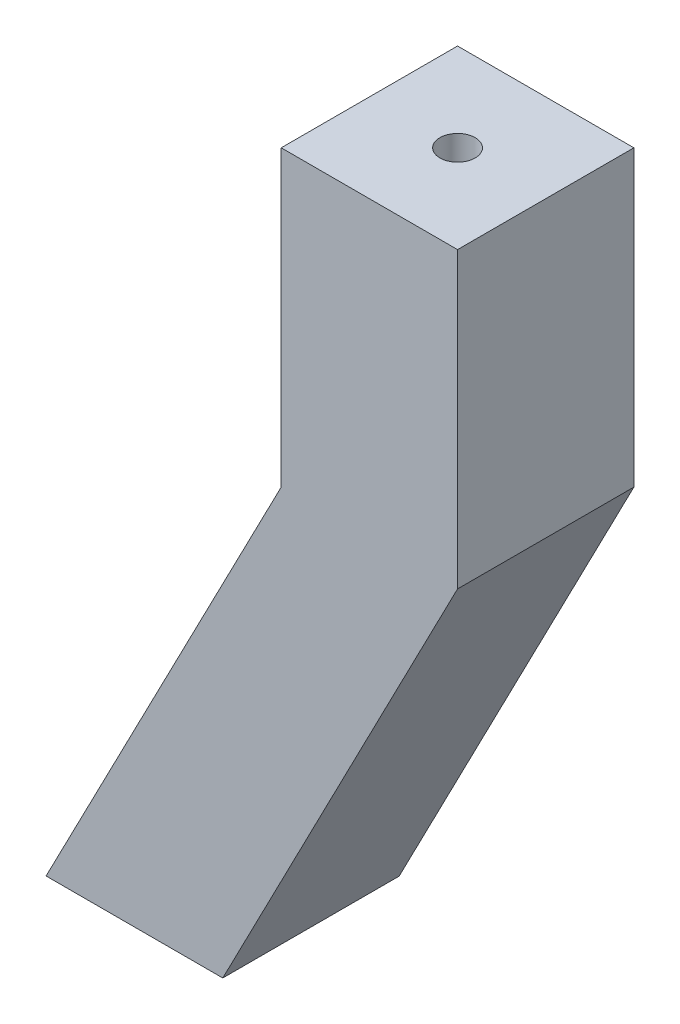
SolidWorks part; units mm, degrees
ref_plane "前视基准面" through (0, 0, 0) normal (0, 0, 1) x (1, 0, 0)
ref_plane "上视基准面" through (0, 0, 0) normal (0, 1, 0) x (1, 0, 0)
ref_plane "右视基准面" through (0, 0, 0) normal (1, 0, 0) x (0, 0, -1)
other "Configuration Table"
sketch "草图1" plane through (0, 0, 0) normal (0, 1, 0) x (1, 0, 0)
  line L1 (-15, 15) -> (15, 15)
  line L2 (-15, 15) -> (-15, -15)
  line L3 (-15, -15) -> (15, -15)
  line L4 (15, 15) -> (15, -15)
  line L5 (-15, 15) -> (15, -15) construction
  line L6 (-15, -15) -> (15, 15) construction
  point P0 (0, 0)
  dimension "D1" = 30
  dimension "D2" = 30
extrude "凸台-拉伸1" add sketch "草图1" along normal blind 50 contours L2 L1 L4 L3
sketch "草图3" plane through (-15, 0, 0) normal (-1, 0, 0) x (0, 0, 1)
  line L0 (-15, 50) -> (-15, 0) construction
  line L1 (-15, 10) -> (15, 10)
  line L2 (-15, 10) -> (-15, -77.3015)
  line L3 (-15, -77.3015) -> (15, -77.3015)
  line L4 (15, 10) -> (15, -77.3015)
  dimension "D1" = 30
  dimension "D2" = 40
extrude "凸台-拉伸2" add sketch "草图3" along normal blind 40 contours L2 L1 L4 L3
sketch "草图4" plane through (-15, 0, 0) normal (1, 0, 0) x (0, 0, -1)
  line L0 (15, 0) -> (-15, 0) construction
  line L1 (-15, 0) -> (15, 0)
  line L2 (-15, 0) -> (-15, -77.3015)
  line L3 (-15, -77.3015) -> (15, -77.3015)
  line L4 (15, 0) -> (15, -77.3015)
  line L5 (15, 0) -> (-15, 0) construction
extrude "凸台-拉伸3" add sketch "草图4" along normal blind 30
sketch "草图5" plane through (0, 0, 15) normal (0, 0, 1) x (1, 0, 0)
  line L0 (15, 0) -> (-25, -77.3015)
  line L1 (15, 0) -> (-15, 0)
  line L2 (-25, -77.3015) -> (-55, -77.3015)
  line L3 (-15, 0) -> (-55, -77.3015)
  line L4 (15, 50) -> (15, -77.3015) construction
  line L5 (-55, -77.3015) -> (15, -77.3015) construction
  dimension "D1" = 30
sketch "草图7" plane through (0, 0, 15) normal (0, 0, 1) x (1, 0, 0)
  line L1 (-55, 10) -> (-15, 10)
  line L2 (-55, 10) -> (-55, 0)
  line L3 (-55, 0) -> (-15, 0)
  line L4 (-15, 10) -> (-15, 0)
extrude "切除-拉伸1" cut sketch "草图7" against normal blind 30
sketch "草图8" plane through (0, 0, 15) normal (0, 0, 1) x (1, 0, 0)
  line L0 (-15, 0) -> (-55, 0)
  line L1 (-15, 0) -> (-55.2414, -77.7475)
  line L2 (-55, 0) -> (-95.2414, -77.7475)
  line L3 (-55.2414, -77.7475) -> (-95.2414, -77.7475)
extrude "切除-拉伸2" cut sketch "草图8" against normal blind 30
sketch "草图9" plane through (0, 0, 15) normal (0, 0, 1) x (1, 0, 0)
  line L0 (15, 0) -> (-26.1252, -79.5827)
  line L1 (15, 0) -> (66.7514, 0)
  line L2 (-26.1252, -79.5827) -> (25.6261, -79.5827)
  line L3 (66.7514, 0) -> (25.6261, -79.5827)
ref_plane "基准面1" through (15, -77.3015, 15) normal (0, -1, 0) x (-1, 0, 0)
extrude "切除-拉伸5" cut sketch "草图9" against normal blind 30 contours L0 L1 L3 L2
sketch "草图12" plane through (0, -77.3015, 0) normal (0, -1, 0) x (-1, 0, 0)
  line L1 (55, -15) -> (24.9464, -15)
  line L2 (55, -15) -> (55, 15)
  line L3 (55, 15) -> (24.9464, 15)
  line L4 (24.9464, -15) -> (24.9464, 15)
sketch "草图21" plane through (0, 50, 0) normal (0, 1, 0) x (1, 0, 0)
  circle A0 centre (0, 0) radius 3
  dimension "D1" = 6
extrude "切除-拉伸6" cut sketch "草图21" against normal blind 50
sketch3d "3D草图4" plane through (0, 0, 0) normal (0, 0, 1) x (1, 0, 0)
  dimension "D1" = 120
